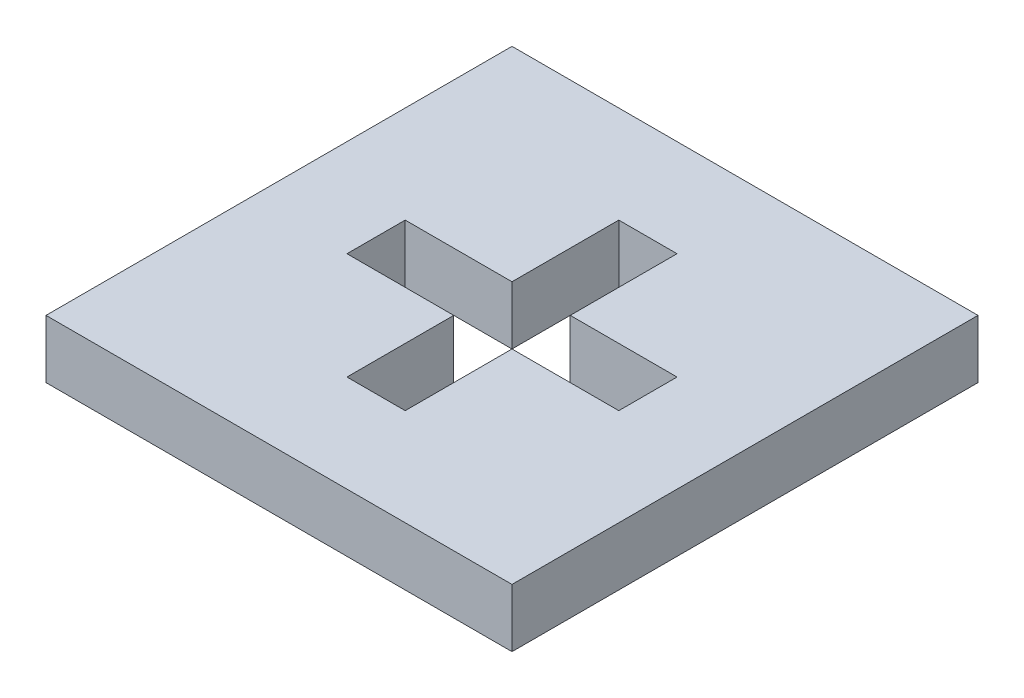
SolidWorks part; units mm, degrees
ref_plane "Front Plane" through (0, 0, 0) normal (0, 0, 1) x (1, 0, 0)
ref_plane "Top Plane" through (0, 0, 0) normal (0, 1, 0) x (1, 0, 0)
ref_plane "Right Plane" through (0, 0, 0) normal (1, 0, 0) x (0, 0, -1)
sketch "Sketch1" plane through (0, 0, 0) normal (0, 1, 0) x (1, 0, 0)
  line L1 (0, 0) -> (50.8, 0)
  line L2 (0, 0) -> (0, 50.8)
  line L3 (0, 50.8) -> (50.8, 50.8)
  line L4 (50.8, 0) -> (50.8, 50.8)
  line L5 (25.4, 50.8) -> (25.4, 0) construction
  line L6 (0, 25.4) -> (50.8, 25.4) construction
  point P80 (25.4, 25.4)
  dimension "D1" = 50.8
extrude "Boss-Extrude1" add sketch "Sketch1" along normal blind 6.35
sketch "Sketch2" plane through (0, 6.35, 0) normal (0, 1, 0) x (1, 0, 0)
  line L0 (10.5833, 50.8) -> (10.5833, 0) construction
  line L3 (50.8, 50.8) -> (0, 50.8) construction
  line L11 (0, 0) -> (50.8, 0) construction
  line L12 (0, 50.8) -> (0, 0) construction
  line L17 (0, 10.5833) -> (50.8, 10.5833) construction
  line L18 (50.8, 0) -> (50.8, 50.8) construction
  line L22 (40.2167, 50.8) -> (40.2167, 0) construction
  line L23 (0, 40.2167) -> (50.8, 40.2167) construction
  line L24 (25.4, 40.2167) -> (25.4, 10.5833) construction
  line L25 (10.5833, 25.4) -> (40.2167, 25.4) construction
  line L26 (28.575, 28.575) -> (40.2167, 28.575)
  line L27 (22.225, 40.2167) -> (28.575, 40.2167)
  line L28 (22.225, 40.2167) -> (22.225, 28.575)
  line L29 (22.225, 10.5833) -> (28.575, 10.5833)
  line L30 (28.575, 40.2167) -> (28.575, 28.575)
  line L31 (25.4, 10.5833) -> (25.4, 40.2167) construction
  line L32 (22.225, 25.4) -> (28.575, 25.4) construction
  line L33 (10.5833, 28.575) -> (22.225, 28.575)
  line L34 (10.5833, 28.575) -> (10.5833, 22.225)
  line L35 (10.5833, 22.225) -> (22.225, 22.225)
  line L36 (40.2167, 28.575) -> (40.2167, 22.225)
  line L37 (25.4, 22.225) -> (25.4, 28.575) construction
  line L38 (10.5833, 25.4) -> (40.2167, 25.4) construction
  line L39 (28.575, 22.225) -> (40.2167, 22.225)
  line L40 (28.575, 22.225) -> (28.575, 10.5833)
  line L41 (22.225, 22.225) -> (22.225, 10.5833)
  point P240 (25.4, 25.4)
  point P531 (25.4, 25.4)
  dimension "D1" = 10.5833
  dimension "D2" = 10.5833
  dimension "D3" = 10.5833
  dimension "D4" = 10.5833
  dimension "D5" = 6.35
  dimension "D6" = 6.35
extrude "Cut-Extrude1" cut sketch "Sketch2" against normal blind 6.35
equation "\"Stock Thickness\"= .25in"
equation "\"D1@Boss-Extrude1\"=\"Stock Thickness\""
equation "\"D1@Cut-Extrude1\"=\"Stock Thickness\""
equation "\"D1@Sketch2\"=\"D1@Sketch1\"/3 - \"Stock Thickness\""
equation "\"D2@Sketch2\"=\"D1@Sketch1\"/3 - \"Stock Thickness\""
equation "\"D3@Sketch2\"=\"D2@Sketch2\""
equation "\"D4@Sketch2\"=\"D1@Sketch2\""
equation "\"D5@Sketch2\"=\"Stock Thickness\""
equation "\"D6@Sketch2\"=\"Stock Thickness\""
